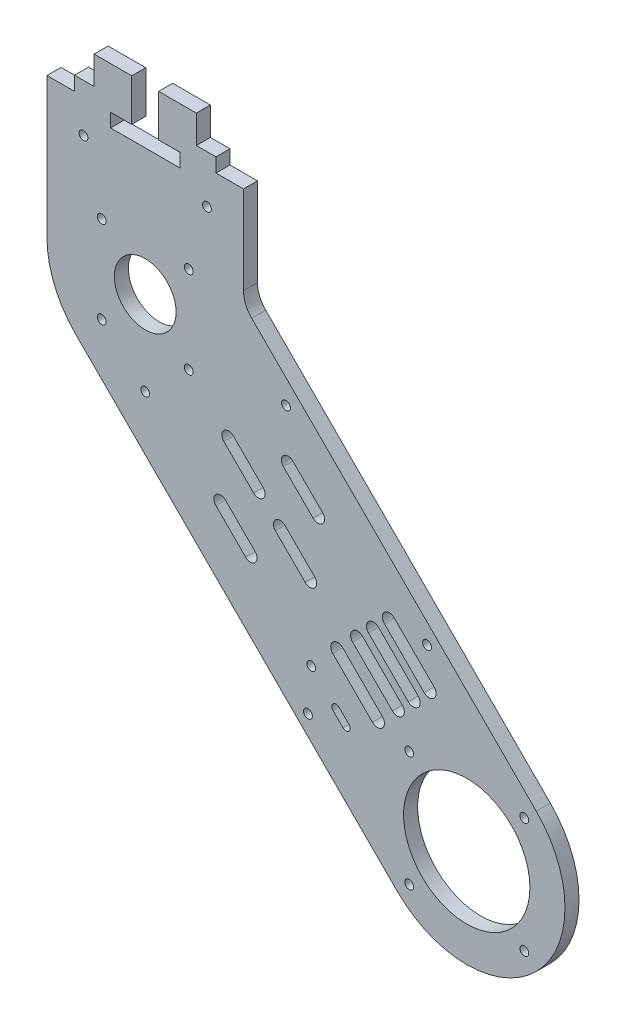
SolidWorks part; units mm, degrees
ref_plane "Front Plane" through (0, 0, 0) normal (0, 0, 1) x (1, 0, 0)
ref_plane "Top Plane" through (0, 0, 0) normal (0, 1, 0) x (1, 0, 0)
ref_plane "Right Plane" through (0, 0, 0) normal (1, 0, 0) x (0, 0, -1)
sketch "Sketch1" plane through (0, 0, 0) normal (0, 0, 1) x (1, 0, 0)
  line L0 (0, 0) -> (35, 0) construction
  line L1 (0, 0) -> (0, 35) construction
  line L2 (0, 0) -> (24.7487, 24.7487) construction
  line L3 (0, 0) -> (-24.7487, -24.7487) construction
  line L4 (-24.7487, -24.7487) -> (-139.3, 89.8026)
  line L5 (0, 0) -> (24.7487, -24.7487) construction
  line L6 (-139.3, 89.8026) -> (-114.5513, 114.5513) construction
  line L7 (24.7487, 24.7487) -> (-54.6728, 104.1703)
  line L8 (-33.234, 51.6188) -> (-19.0919, 37.4767) construction
  line L9 (-31.4663, 53.3866) -> (-17.3241, 39.2444)
  line L10 (-35.0018, 49.851) -> (-20.8597, 35.7089)
  line L11 (-114.5513, 114.5513) -> (0, 0) construction
  line L12 (-38.8909, 45.9619) -> (-24.7487, 31.8198) construction
  line L13 (-37.1231, 47.7297) -> (-22.981, 33.5876)
  line L14 (-40.6586, 44.1942) -> (-26.5165, 30.052)
  line L15 (-31.8198, 38.8909) -> (-10.6066, 60.1041) construction
  line L16 (-27.5772, 57.2756) -> (-13.435, 43.1335) construction
  line L17 (-25.8094, 59.0434) -> (-11.6673, 44.9013)
  line L18 (-29.3449, 55.5079) -> (-15.2028, 41.3657)
  line L19 (-31.8198, 38.8909) -> (-60.1041, 10.6066) construction
  line L20 (-45.9619, 38.8909) -> (-31.8198, 24.7487) construction
  line L21 (-44.1942, 40.6586) -> (-30.052, 26.5165)
  line L22 (-47.7297, 37.1231) -> (-33.5876, 22.981)
  line L23 (-84.8528, 84.8528) -> (-74.2462, 74.2462) construction
  line L24 (-83.1558, 86.5499) -> (-72.5492, 75.9433)
  line L25 (-86.5499, 83.1558) -> (-75.9433, 72.5492)
  line L26 (-64.3969, 105.3087) -> (-109.6016, 60.1041) construction
  line L27 (-66.468, 66.468) -> (-55.8614, 55.8614) construction
  line L28 (-64.771, 68.1651) -> (-54.1644, 57.5585)
  line L29 (-68.1651, 64.771) -> (-57.5585, 54.1644)
  line L30 (-63.6396, 87.6812) -> (-53.033, 77.0746) construction
  line L33 (-74.2462, 74.2462) -> (-49.4975, 98.9949) construction
  line L34 (-70.3571, 70.3571) -> (-45.6084, 95.1059) construction
  line L35 (-61.9426, 89.3783) -> (-51.336, 78.7717)
  line L36 (-65.3367, 85.9842) -> (-54.7301, 75.3776)
  line L37 (-87.6812, 63.6396) -> (-77.0746, 53.033) construction
  line L38 (-89.3783, 61.9426) -> (-78.7717, 51.336)
  line L39 (-85.9842, 65.3367) -> (-75.3776, 54.7301)
  line L40 (-114.5513, 114.5513) -> (-207.3962, 114.5513) construction
  line L41 (-149.5513, 114.5513) -> (-149.5513, 164.5513)
  line L42 (-114.5513, 114.5513) -> (-8.6743, 114.5513) construction
  line L43 (-79.5513, 133.1909) -> (-79.5513, 165.6653)
  line L44 (-114.5513, 114.5513) -> (-79.5513, 149.5513) construction
  line L45 (-54.6728, 104.1703) -> (-76.6224, 126.1198)
  line L46 (-114.5513, 114.5513) -> (-146.8871, 101.1574) construction
  line L47 (-146.8871, 101.1574) -> (-49.8797, 141.3391) construction
  line L48 (-114.5513, 114.5513) -> (-114.5513, 82.9763) construction
  line L49 (-132.7513, 174.5513) -> (-119.3513, 174.5513) construction
  line L50 (-79.5513, 165.6653) -> (-79.5513, 174.5513)
  line L51 (-119.3513, 169.5513) -> (-119.3513, 164.5513)
  line L52 (-114.5513, 114.5513) -> (-114.5513, 174.5513) construction
  line L53 (-119.3513, 174.5513) -> (-132.7513, 174.5513)
  line L54 (-126.9013, 164.5513) -> (-102.2013, 164.5513)
  line L55 (-126.9013, 164.5513) -> (-126.9013, 159.7013)
  line L56 (-126.9013, 159.7013) -> (-102.2013, 159.7013)
  line L57 (-102.2013, 164.5513) -> (-102.2013, 159.7013)
  line L58 (-139.7513, 169.5513) -> (-132.7513, 169.5513) construction
  line L59 (-46.563, 20.6122) -> (-43.0274, 17.0766) construction
  line L60 (-132.7513, 174.5513) -> (-132.7513, 169.5513) construction
  line L61 (-119.3513, 169.5513) -> (-119.3513, 174.5513)
  line L62 (-114.5513, 174.5513) -> (-96.3513, 174.5513) construction
  line L63 (-114.5513, 159.7013) -> (-114.5513, 164.5513) construction
  line L64 (-126.9013, 162.1263) -> (-102.2013, 162.1263) construction
  line L65 (-149.5513, 164.5513) -> (-79.5513, 164.5513) construction
  line L66 (-132.7513, 169.5513) -> (-139.7513, 169.5513)
  line L67 (-139.7513, 169.5513) -> (-139.7513, 164.5513)
  line L68 (-139.7513, 164.5513) -> (-149.5513, 164.5513)
  line L69 (-132.7513, 169.5513) -> (-132.7513, 174.5513)
  line L70 (-109.7513, 169.5513) -> (-109.7513, 174.5513)
  line L71 (-109.7513, 174.5513) -> (-96.3513, 174.5513)
  line L72 (-96.3513, 169.5513) -> (-96.3513, 174.5513)
  line L73 (-96.3513, 169.5513) -> (-89.3513, 169.5513)
  line L74 (-89.3513, 169.5513) -> (-89.3513, 164.5513)
  line L75 (-89.3513, 164.5513) -> (-79.5513, 164.5513)
  line L76 (-119.3513, 169.5513) -> (-109.7513, 169.5513) construction
  line L77 (-96.3513, 169.5513) -> (-89.3513, 169.5513) construction
  line L78 (-45.5023, 21.6728) -> (-41.9668, 18.1373)
  line L79 (-47.6236, 19.5515) -> (-44.0881, 16.016)
  line L80 (-119.3513, 164.5513) -> (-109.7513, 164.5513)
  line L81 (-109.7513, 164.5513) -> (-109.7513, 169.5513)
  circle A0 centre (0, 0) radius 22.5
  arc A1 (-24.7487, -24.7487) -> (24.7487, 24.7487) centre (0, 0) ccw
  circle A2 centre (-114.5513, 114.5513) radius 11
  circle A3 centre (20.5061, -20.5061) radius 1.575
  circle A4 centre (-20.5061, -20.5061) radius 1.575
  circle A5 centre (-20.5061, 20.5061) radius 1.575
  circle A6 centre (20.5061, 20.5061) radius 1.575
  arc A7 (-31.4663, 53.3866) -> (-35.0018, 49.851) centre (-33.234, 51.6188) ccw
  arc A8 (-20.8597, 35.7089) -> (-17.3241, 39.2444) centre (-19.0919, 37.4767) ccw
  arc A9 (-37.1231, 47.7297) -> (-40.6586, 44.1942) centre (-38.8909, 45.9619) ccw
  arc A10 (-26.5165, 30.052) -> (-22.981, 33.5876) centre (-24.7487, 31.8198) ccw
  arc A11 (-25.8094, 59.0434) -> (-29.3449, 55.5079) centre (-27.5772, 57.2756) ccw
  arc A12 (-15.2028, 41.3657) -> (-11.6673, 44.9013) centre (-13.435, 43.1335) ccw
  arc A13 (-44.1942, 40.6586) -> (-47.7297, 37.1231) centre (-45.9619, 38.8909) ccw
  arc A14 (-33.5876, 22.981) -> (-30.052, 26.5165) centre (-31.8198, 24.7487) ccw
  circle A15 centre (-14.1421, 56.5685) radius 1.575
  circle A16 centre (-56.5685, 14.1421) radius 1.575
  circle A17 centre (-64.3969, 105.3087) radius 1.575
  arc A18 (-83.1558, 86.5499) -> (-86.5499, 83.1558) centre (-84.8528, 84.8528) ccw
  arc A19 (-75.9433, 72.5492) -> (-72.5492, 75.9433) centre (-74.2462, 74.2462) ccw
  arc A20 (-64.771, 68.1651) -> (-68.1651, 64.771) centre (-66.468, 66.468) ccw
  arc A21 (-57.5585, 54.1644) -> (-54.1644, 57.5585) centre (-55.8614, 55.8614) ccw
  arc A24 (-61.9426, 89.3783) -> (-65.3367, 85.9842) centre (-63.6396, 87.6812) ccw
  arc A25 (-54.7301, 75.3776) -> (-51.336, 78.7717) centre (-53.033, 77.0746) ccw
  arc A26 (-89.3783, 61.9426) -> (-85.9842, 65.3367) centre (-87.6812, 63.6396) cw
  arc A27 (-75.3776, 54.7301) -> (-78.7717, 51.336) centre (-77.0746, 53.033) cw
  arc A29 (-149.5513, 114.5513) -> (-139.3, 89.8026) centre (-114.5513, 114.5513) ccw
  arc A31 (-76.6224, 126.1198) -> (-79.5513, 133.1909) centre (-69.5513, 133.1909) cw
  circle A32 centre (-99.0513, 130.0513) radius 1.575
  circle A33 centre (-99.0513, 99.0513) radius 1.575
  circle A34 centre (-130.0513, 99.0513) radius 1.575
  circle A35 centre (-130.0513, 130.0513) radius 1.575
  circle A36 centre (-114.5513, 84.5513) radius 1.575
  circle A37 centre (-136.5513, 152.5513) radius 1.575
  circle A38 centre (-92.5513, 152.5513) radius 1.575
  circle A39 centre (-55.4018, 29.451) radius 1.575
  arc A40 (-45.5023, 21.6728) -> (-47.6236, 19.5515) centre (-46.563, 20.6122) ccw
  arc A41 (-44.0881, 16.016) -> (-41.9668, 18.1373) centre (-43.0274, 17.0766) ccw
  point P23 (0, 0)
  point P24 (-26.163, 44.5477)
  point P31 (-31.8198, 38.8909)
  point P42 (-20.5061, 50.2046)
  point P47 (-38.8909, 31.8198)
  point P59 (-79.5495, 79.5495)
  point P68 (-61.1647, 61.1647)
  point P76 (-58.3363, 82.3779)
  point P92 (-82.3779, 58.3363)
  point P107 (-79.5513, 129.0488)
  point P116 (-114.5513, 114.5513)
  point P123 (-114.5513, 162.1263)
  point P144 (-44.7952, 18.8444)
  dimension "D1" = 45
  dimension "D2" = 70
  dimension "D6" = 22
  dimension "D7" = 3.15
  dimension "D12" = 2.5
  dimension "D15" = 2.5
  dimension "D20" = 3.15
  dimension "D22" = 3.15
  dimension "D25" = 2.4
  dimension "D29" = 2.4
  dimension "D30" = 17
  dimension "D31" = 5.5
  dimension "D35" = 35.1835
  dimension "D36" = 32.1163
  dimension "D37" = 10
  dimension "D38" = 3.15
  dimension "D41" = 3.15
  dimension "D43" = 3.15
  dimension "D46" = 3.15
  dimension "D58" = 1.5
  dimension "D3" = 45
  dimension "D4" = 180
  dimension "D5" = 162
  dimension "D8" = 29
  dimension "D10" = 35
  dimension "D11" = 20
  dimension "D13" = 5
  dimension "D14" = 20
  dimension "D16" = 50
  dimension "D17" = 8
  dimension "D18" = 8
  dimension "D19" = 10
  dimension "D21" = 5
  dimension "D23" = 6.071
  dimension "D24" = 70
  dimension "D26" = 15
  dimension "D27" = 11
  dimension "D28" = 15
  dimension "D32" = 70
  dimension "D33" = 35
  dimension "D34" = 180
  dimension "D39" = 15.5
  dimension "D42" = 30
  dimension "D44" = 13
  dimension "D45" = 38
  dimension "D47" = 18.2
  dimension "D48" = 12.425
  dimension "D49" = 10
  dimension "D50" = 24.7
  dimension "D51" = 5
  dimension "D52" = 13.4
  dimension "D53" = 5
  dimension "D54" = 25.2
  dimension "D55" = 60
  dimension "D56" = 16.65
  dimension "D57" = 16.65
  dimension "D59" = 5
  dimension "D60" = 12.5
  dimension "D9" = 4
  dimension "D40" = 4
extrude "Boss-Extrude1" add sketch "Sketch1" against normal blind 5
sketch "Sketch2" plane through (0, 0, 0) normal (0, 0, 1) x (1, 0, 0)
  line L0 (-132.7513, 174.5513) -> (-132.7513, 179.5513)
  line L1 (-132.7513, 179.5513) -> (-119.3513, 179.5513)
  line L2 (-119.3513, 179.5513) -> (-119.3513, 174.5513)
  line L3 (-119.3513, 174.5513) -> (-132.7513, 174.5513)
  line L4 (-109.7513, 174.5513) -> (-109.7513, 179.5513)
  line L5 (-109.7513, 179.5513) -> (-96.3513, 179.5513)
  line L6 (-96.3513, 179.5513) -> (-96.3513, 174.5513)
  line L7 (-109.7513, 174.5513) -> (-96.3513, 174.5513)
  dimension "D1" = 5
extrude "Boss-Extrude2" add sketch "Sketch2" against normal blind 5
